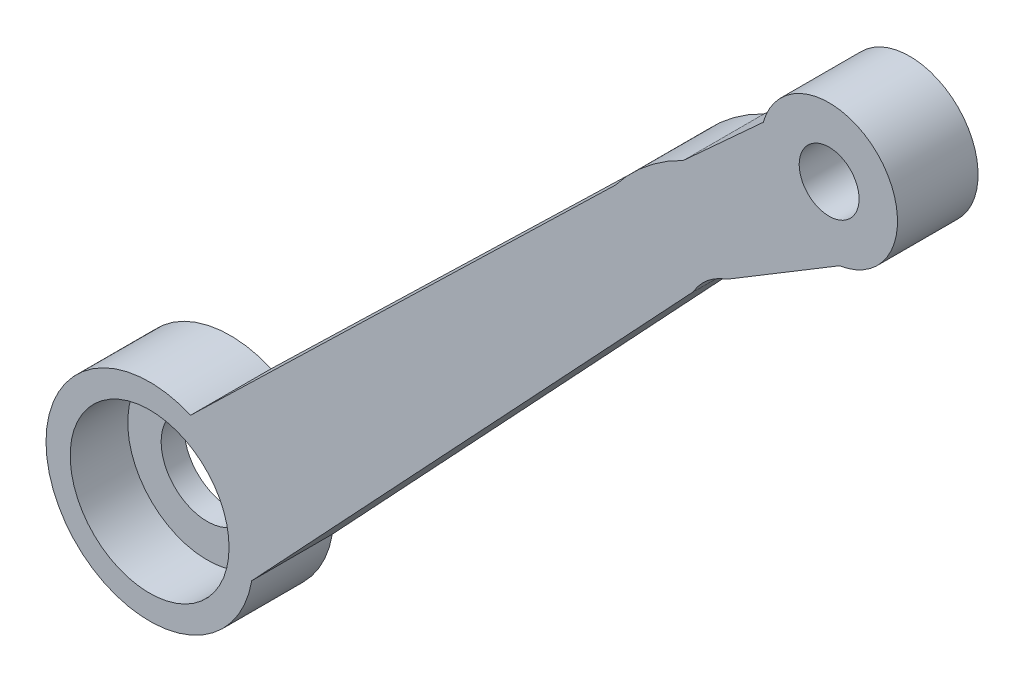
SolidWorks part; units mm, degrees
ref_plane "Front Plane" through (0, 0, 0) normal (0, 0, 1) x (1, 0, 0)
ref_plane "Top Plane" through (0, 0, 0) normal (0, 1, 0) x (1, 0, 0)
ref_plane "Right Plane" through (0, 0, 0) normal (1, 0, 0) x (0, 0, -1)
sketch "Sketch1" plane through (0, 0, 0) normal (0, 0, 1) x (1, 0, 0)
  line L8 (-116.1165, -73.1162) -> (-77.7804, -32.2217)
  line L9 (-74.8335, -29.7976) -> (-65.0583, -23.8962)
  line L10 (-71.6872, -16.4176) -> (-78.6359, -22.7631)
  line L11 (-84.5297, -27.5637) -> (-121.4306, -63.3278)
  circle A0 centre (-65.9692, -18.0264) radius 2.6
  circle A1 centre (-124.987, -71.5953) radius 6.9
  arc A2 (-121.4306, -63.3278) -> (-116.1165, -73.1162) centre (-124.987, -71.5953) ccw
  arc A9 (-74.8335, -29.7976) -> (-77.7804, -32.2217) centre (-73.0977, -34.911) ccw
  arc A10 (-65.0583, -23.8962) -> (-71.6872, -16.4176) centre (-65.9692, -18.0264) ccw
  arc A11 (-78.6359, -22.7631) -> (-84.5297, -27.5637) centre (-71.4001, -37.665) ccw
extrude "Boss-Extrude1" add sketch "Sketch1" along normal blind 5
sketch "Sketch2" plane through (0, 0, 0) normal (0, 0, -1) x (-1, 0, 0)
  line L4 (121.4306, -63.3278) -> (84.5297, -27.5637)
  line L5 (78.6359, -22.7631) -> (71.6872, -16.4176)
  line L6 (65.0583, -23.8962) -> (74.8335, -29.7976)
  line L7 (77.7804, -32.2217) -> (116.1165, -73.1162)
  line L8 (121.4306, -63.3278) -> (84.5297, -27.5637)
  line L9 (78.6359, -22.7631) -> (71.6872, -16.4176)
  line L10 (65.0583, -23.8962) -> (74.8335, -29.7976)
  line L11 (77.7804, -32.2217) -> (116.1165, -73.1162)
  circle A0 centre (124.987, -71.5953) radius 4
  circle A1 centre (65.9692, -18.0264) radius 2.6
  arc A4 (116.1165, -73.1162) -> (121.4306, -63.3278) centre (124.987, -71.5953) ccw
  arc A5 (84.5297, -27.5637) -> (78.6359, -22.7631) centre (71.4001, -37.665) ccw
  arc A6 (71.6872, -16.4176) -> (65.0583, -23.8962) centre (65.9692, -18.0264) ccw
  arc A7 (77.7804, -32.2217) -> (74.8335, -29.7976) centre (73.0977, -34.911) ccw
  arc A8 (116.1165, -73.1162) -> (121.4306, -63.3278) centre (124.987, -71.5953) ccw
  arc A9 (84.5297, -27.5637) -> (78.6359, -22.7631) centre (71.4001, -37.665) ccw
  arc A10 (71.6872, -16.4176) -> (65.0583, -23.8962) centre (65.9692, -18.0264) ccw
  arc A11 (77.7804, -32.2217) -> (74.8335, -29.7976) centre (73.0977, -34.911) ccw
  dimension "D2" = 8
  dimension "D3" = 5.2
  dimension "D1" = 0
extrude "Boss-Extrude2" add sketch "Sketch2" along normal blind 2
